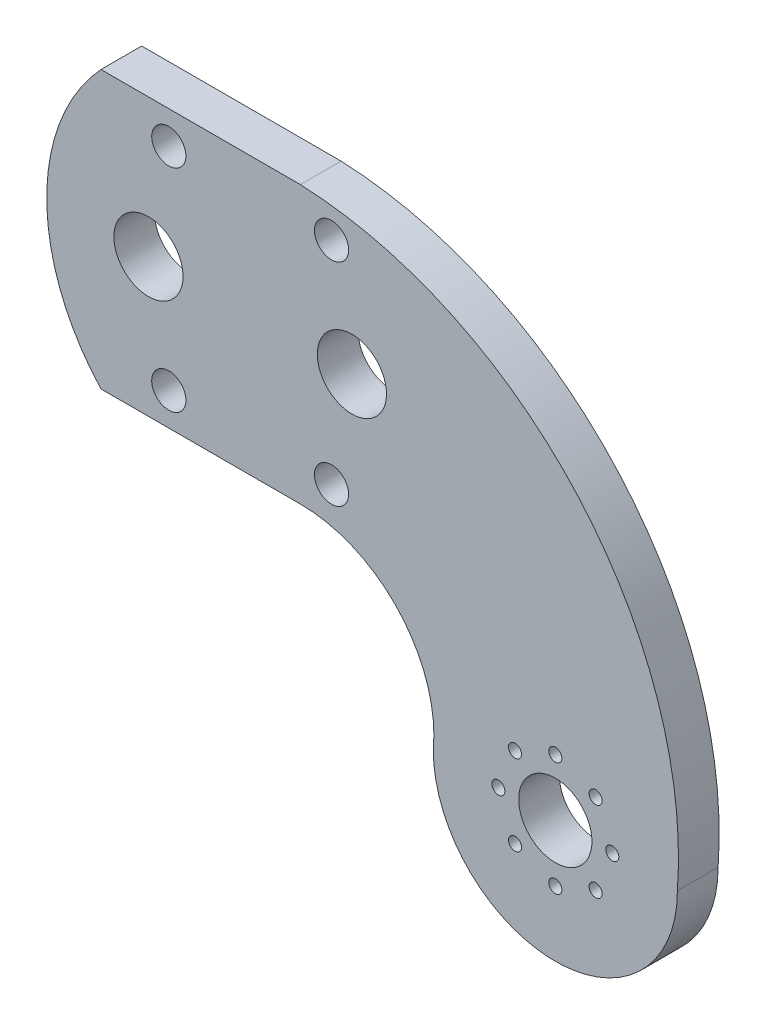
SolidWorks part; units mm, degrees
ref_plane "Front Plane" through (0, 0, 0) normal (0, 0, 1) x (1, 0, 0)
ref_plane "Top Plane" through (0, 0, 0) normal (0, 1, 0) x (1, 0, 0)
ref_plane "Right Plane" through (0, 0, 0) normal (1, 0, 0) x (0, 0, -1)
sketch "Sketch1" plane through (0, 0, 0) normal (0, 0, 1) x (1, 0, 0)
  line L0 (-25, 0) -> (0, 0) construction
  line L1 (-12.5, 0) -> (-12.5, -11.0721) construction
  line L2 (-12.5, 0) -> (-12.5, 17) construction
  line L3 (-30.8303, 17) -> (-6.3318, 17)
  line L4 (-30.8303, -17) -> (-6.3318, -17)
  circle A0 centre (0, 0) radius 4.25
  circle A1 centre (-25, 0) radius 4.25
  circle A2 centre (-22.5, -13) radius 2.1
  circle A3 centre (-2.5, -13) radius 2.1
  circle A4 centre (-2.5, 13) radius 2.1
  circle A5 centre (-22.5, 13) radius 2.1
  arc A6 (-30.8303, 17) -> (-30.8303, -17) centre (-12.5, 0) ccw
  arc A29 (10, -35) -> (40, -35) centre (25, -35) ccw
  arc A30 (-6.3318, -17) -> (10, -35) centre (-6.3318, -33.4091) cw
  arc A31 (-6.3318, 17) -> (40, -35) centre (-8.3306, -31.4217) cw
  point P4 (-12.5, 0)
  arc B0 (15.5, -35) -> (34.5, -35) centre (25, -35) ccw
  arc B1 (34.5, -35) -> (15.5, -35) centre (25, -35) ccw
  arc B2 (20.5, -35) -> (29.5, -35) centre (25, -35) ccw
  arc B3 (29.5, -35) -> (20.5, -35) centre (25, -35) ccw
  arc B4 (20.8503, -30.0503) -> (19.2503, -30.0503) centre (20.0503, -30.0503) ccw
  arc B5 (19.2503, -30.0503) -> (20.8503, -30.0503) centre (20.0503, -30.0503) ccw
  arc B6 (18.8, -35) -> (17.2, -35) centre (18, -35) ccw
  arc B7 (17.2, -35) -> (18.8, -35) centre (18, -35) ccw
  arc B8 (20.8503, -39.9497) -> (19.2503, -39.9497) centre (20.0503, -39.9497) ccw
  arc B9 (19.2503, -39.9497) -> (20.8503, -39.9497) centre (20.0503, -39.9497) ccw
  arc B10 (24.2, -42) -> (25.8, -42) centre (25, -42) ccw
  arc B11 (25.8, -42) -> (24.2, -42) centre (25, -42) ccw
  arc B12 (29.1497, -39.9497) -> (30.7497, -39.9497) centre (29.9497, -39.9497) ccw
  arc B13 (30.7497, -39.9497) -> (29.1497, -39.9497) centre (29.9497, -39.9497) ccw
  arc B14 (31.2, -35) -> (32.8, -35) centre (32, -35) ccw
  arc B15 (32.8, -35) -> (31.2, -35) centre (32, -35) ccw
  arc B16 (29.1497, -30.0503) -> (30.7497, -30.0503) centre (29.9497, -30.0503) ccw
  arc B17 (30.7497, -30.0503) -> (29.1497, -30.0503) centre (29.9497, -30.0503) ccw
  arc B18 (25.8, -28) -> (24.2, -28) centre (25, -28) ccw
  arc B19 (24.2, -28) -> (25.8, -28) centre (25, -28) ccw
  dimension "D1" = 8.5
  dimension "D2" = 8.5
  dimension "D3" = 25
  dimension "D4" = 2.5
  dimension "D5" = 13
  dimension "D6" = 4.2
  dimension "D7" = 50
  dimension "D9" = 25
  dimension "D10" = 35
  dimension "D8" = 17
sketch_block_instance "Block1-1"
sketch_block "Block1"
extrude "Boss-Extrude1" add sketch "Sketch1" along normal blind 5
move or copy body "Body-Move/Copy1" [suppressed] bodies to move or copy 101
